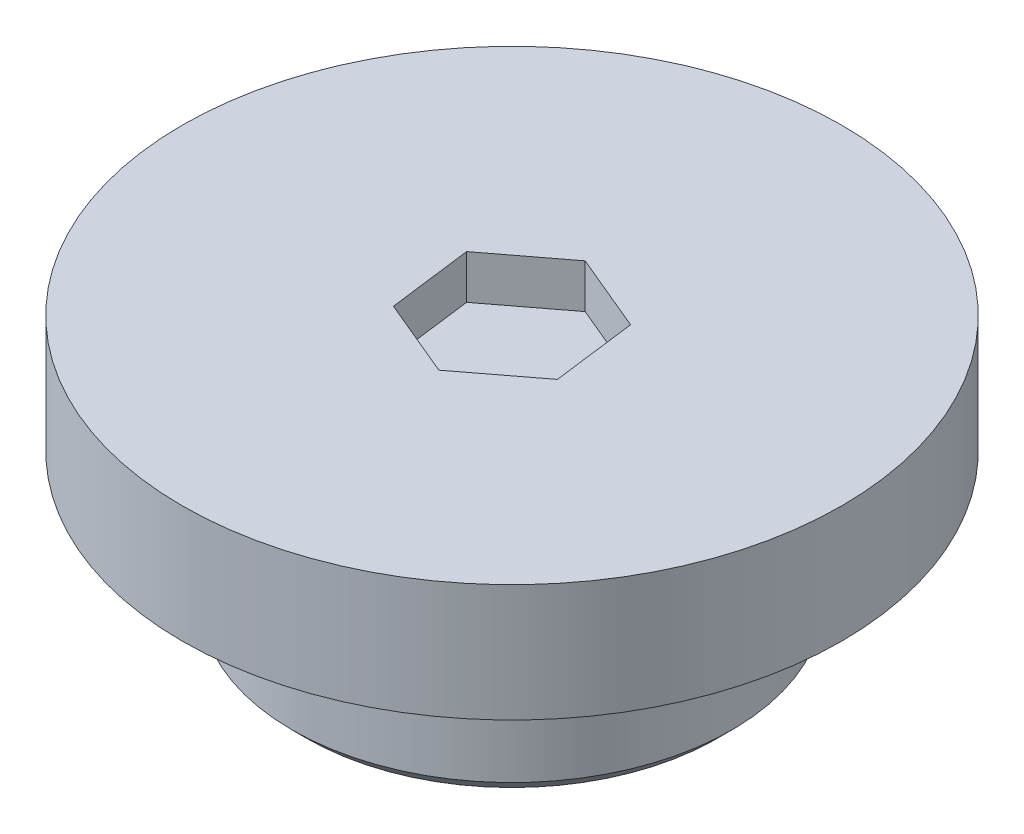
SolidWorks part; units mm, degrees
material "7075-T6 (SN)"
ref_plane "Front Plane" through (0, 0, 0) normal (0, 0, 1) x (1, 0, 0)
ref_plane "Top Plane" through (0, 0, 0) normal (0, 1, 0) x (1, 0, 0)
ref_plane "Right Plane" through (0, 0, 0) normal (1, 0, 0) x (0, 0, -1)
sketch "Sketch1" plane through (0, 0, 0) normal (0, 1, 0) x (1, 0, 0)
  circle A0 centre (0, 0) radius 15
  dimension "D1" = 30
extrude "Boss-Extrude1" add sketch "Sketch1" along normal blind 10
sketch "Sketch2" plane through (0, 10, 0) normal (0, 1, 0) x (1, 0, 0)
  circle A0 centre (0, 0) radius 22.5
  dimension "D1" = 45
extrude "Boss-Extrude2" add sketch "Sketch2" along normal blind 8 contours A0
chamfer "Chamfer1" distance 1 angle 45 1 edges at (0, 0, 15)
sketch "Sketch3" plane through (0, 0, 0) normal (0, -1, 0) x (1, 0, 0)
  circle A0 centre (0, 0) radius 10
  dimension "D1" = 20
extrude "Cut-Extrude1" cut sketch "Sketch3" against normal up to surface (10 mm away) up to face at (0, 10, 15)
sketch "Sketch4" plane through (0, 18, 0) normal (0, 1, 0) x (1, 0, 0)
  line L1 (5.3262, -2.2282) -> (4.5928, 3.4985)
  line L2 (4.5928, 3.4985) -> (-0.7334, 5.7267)
  line L3 (-0.7334, 5.7267) -> (-5.3262, 2.2282)
  line L4 (-5.3262, 2.2282) -> (-4.5928, -3.4985)
  line L5 (-4.5928, -3.4985) -> (0.7334, -5.7267)
  line L6 (0.7334, -5.7267) -> (5.3262, -2.2282)
  circle A1 centre (0, 0) radius 5 construction
  dimension "D1" = 10
extrude "Cut-Extrude2" cut sketch "Sketch4" against normal blind 3
chamfer "Chamfer2" distance 1 angle 45 1 edges at (0, 0, -10)
